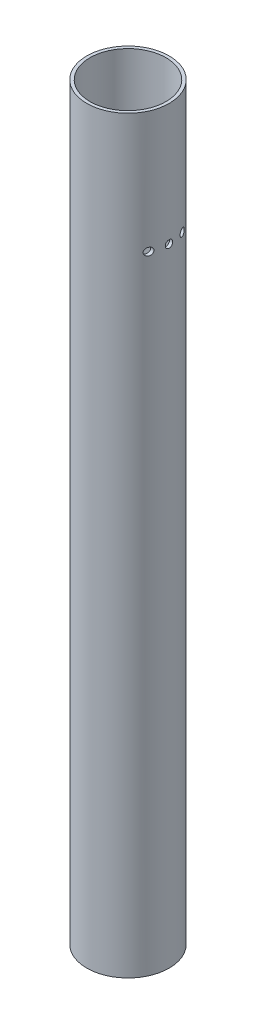
SolidWorks part; units mm, degrees
ref_plane "Front Plane" through (0, 0, 0) normal (0, 0, 1) x (1, 0, 0)
ref_plane "Top Plane" through (0, 0, 0) normal (0, 1, 0) x (1, 0, 0)
ref_plane "Right Plane" through (0, 0, 0) normal (1, 0, 0) x (0, 0, -1)
sketch "Sketch1" plane through (0, 0, 0) normal (0, 1, 0) x (1, 0, 0)
  line L0 (0, 48.6) -> (0, 55)
  circle A0 centre (0, 0) radius 55
  circle A1 centre (0, 0) radius 48.6
  dimension "D1" = 110
  dimension "D2" = 6.4
extrude "Boss-Extrude1" add sketch "Sketch1" along normal mid plane 1000
sketch "Sketch2" plane through (0, 0, 0) normal (0, 1, 0) x (1, 0, 0)
  line L0 (-37.8535, 22.5) -> (37.8535, 22.5)
  line L1 (-37.8535, -30) -> (37.8535, -30)
  line L2 (-37.8535, -30) -> (-37.8535, 30)
  line L3 (-37.8535, 30) -> (37.8535, 30)
  line L4 (37.8535, -30) -> (37.8535, 30)
  line L5 (-37.8535, -30) -> (37.8535, 30) construction
  line L6 (-37.8535, 30) -> (37.8535, -30) construction
  line L7 (-37.8535, 17.5) -> (37.8535, 17.5)
  line L8 (-37.8535, 27.5) -> (37.8535, 27.5)
  line L9 (-37.8535, 0) -> (37.8535, 0) construction
  line L10 (-37.8535, -27.5) -> (37.8535, -27.5)
  line L11 (-37.8535, -22.5) -> (37.8535, -22.5)
  line L12 (-37.8535, -17.5) -> (37.8535, -17.5)
  line L13 (-37.8535, -5) -> (37.8535, -5)
  line L14 (-37.8535, 5) -> (37.8535, 5)
  circle A0 centre (0, 0) radius 48.6 construction
  circle A1 centre (0, 0) radius 48.6 construction
  circle A2 centre (0, 0) radius 48.3
  circle A3 centre (0, 0) radius 15
  point P25 (-37.8535, 22.5)
  point P26 (-37.8535, -22.5)
  point P31 (-37.8535, 0)
  dimension "D3" = 2.5
  dimension "D6" = 30
  dimension "D2" = 60
  dimension "D1" = 0.3
  dimension "D4" = 5
  dimension "D5" = 5
  dimension "D7" = 5
  dimension "D8" = 5
sketch "Sketch3" plane through (0, 0, 0) normal (1, 0, 0) x (0, 0, -1)
  line L0 (0, 337.5) -> (0, 500) construction
  line L1 (48.6, 500) -> (-48.6, 500) construction
  line L2 (48.6, 500) -> (-48.6, 500) construction
  circle A0 centre (0, 337.5) radius 5
  circle A1 centre (22.5, 337.5) radius 5
  circle A2 centre (-22.5, 337.5) radius 5
extrude "Cut-Extrude1" cut sketch "Sketch3" against normal through all both and the other way through all
sketch "Sketch4" plane through (0, 500, 0) normal (0, 1, 0) x (1, 0, 0)
  circle A0 centre (0, 0) radius 50.8
  dimension "D1" = 101.6
extrude "Cut-Extrude2" cut sketch "Sketch4" against normal through all both and the other way through all
